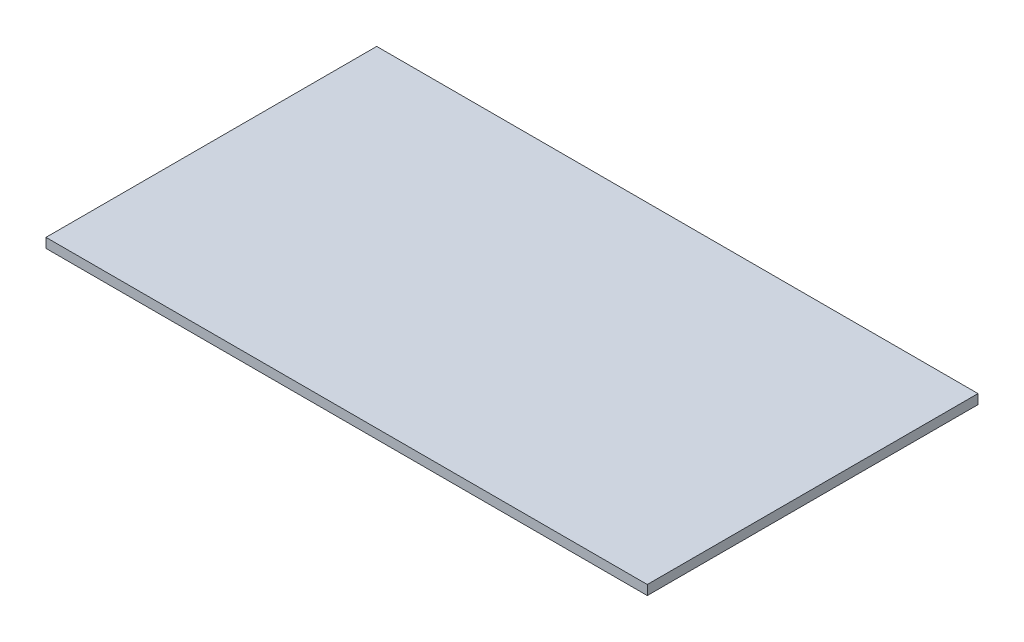
SolidWorks part; units mm, degrees
ref_plane "Front Plane" through (0, 0, 0) normal (0, 0, 1) x (1, 0, 0)
ref_plane "Top Plane" through (0, 0, 0) normal (0, 1, 0) x (1, 0, 0)
ref_plane "Right Plane" through (0, 0, 0) normal (1, 0, 0) x (0, 0, -1)
sketch "Sketch1" plane through (0, 0, 0) normal (0, 1, 0) x (1, 0, 0)
  line L1 (-50, -27.5) -> (50, -27.5)
  line L2 (-50, -27.5) -> (-50, 27.5)
  line L3 (-50, 27.5) -> (50, 27.5)
  line L4 (50, -27.5) -> (50, 27.5)
extrude "Plate_Extrude" add sketch "Sketch1" along normal blind 1.6
equation "\"ValveDiameter\" = 50mm"
equation "\"MotorGearTeeth\" = 40"
equation "\"OutputGearTeeth\" = 80"
equation "\"GearModule\" = 1.5mm"
equation "\"PressureAngle\" = 20deg"
equation "\"GearCenterDistance\" = 90mm"
equation "\"GearWidth\" = 18mm"
equation "\"OutputShaftDiameter\" = 20mm"
equation "\"BearingOD\" = 47mm"
equation "\"BearingWidth\" = 14mm"
equation "\"PlateThickness\" = 6mm"
equation "\"ValveRotation\" = 90deg"
